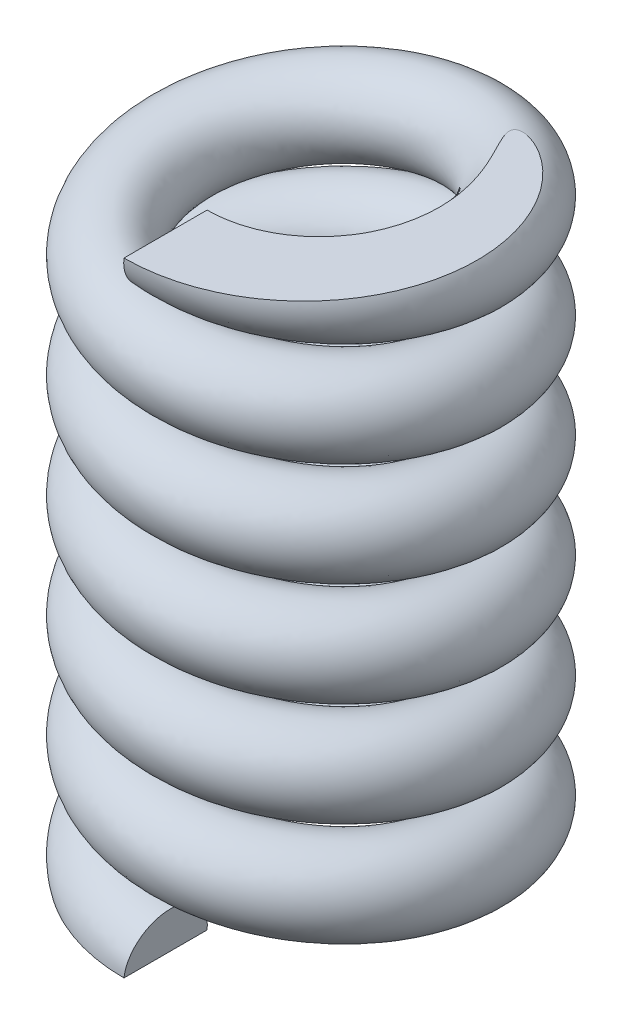
SolidWorks part; units mm, degrees
ref_plane "Front Plane" through (0, 0, 0) normal (0, 0, 1) x (1, 0, 0)
ref_plane "Top Plane" through (0, 0, 0) normal (0, 1, 0) x (1, 0, 0)
ref_plane "Right Plane" through (0, 0, 0) normal (1, 0, 0) x (0, 0, -1)
sketch "Sketch10" plane through (0, 0, 0) normal (0, 1, 0) x (1, 0, 0)
  circle A0 centre (0, 0) radius 3.5
  dimension "D1" = 7
curve "Helix/Spiral3" pitch 2.5 height 15 turns 6
sweep "Sweep2" add path "Helix/Spiral3" circular profile diameter 2 parameters "D3"=2
sketch "Sketch17" plane through (0, 0, 0) normal (0, 1, 0) x (1, 0, 0)
  circle A0 centre (0, 0) radius 7
  dimension "D1" = 14
extrude "Cut-Extrude1" cut sketch "Sketch17" against normal blind 10
ref_plane "Plane2" through (0, 15, 0) normal (0, -1, 0) x (-1, 0, 0)
sketch "Sketch18" plane through (0, 15, 0) normal (0, -1, 0) x (-1, 0, 0)
  circle A0 centre (0, 0) radius 7
  dimension "D1" = 14
extrude "Cut-Extrude2" cut sketch "Sketch18" against normal blind 10
